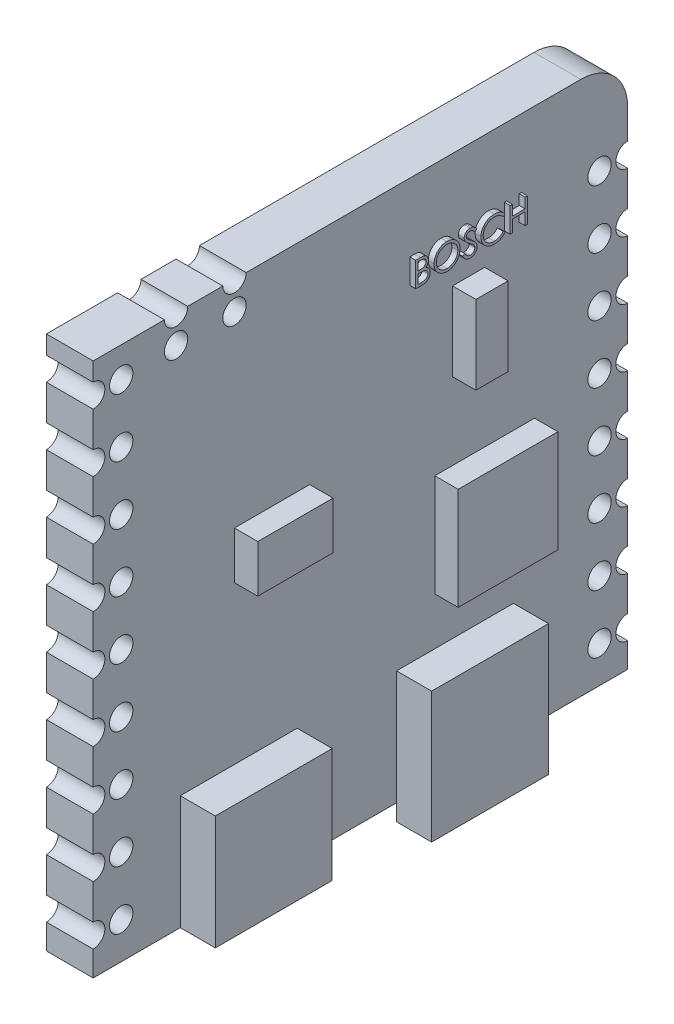
SolidWorks part; units mm, degrees
ref_plane "Front Plane" through (0, 0, 0) normal (0, 0, 1) x (1, 0, 0)
ref_plane "Top Plane" through (0, 0, 0) normal (0, 1, 0) x (1, 0, 0)
ref_plane "Right Plane" through (0, 0, 0) normal (1, 0, 0) x (0, 0, -1)
sketch "Sketch2" plane through (0, 0, 0) normal (1, 0, 0) x (0, 0, -1)
  line L0 (0, 55) -> (0, -55) construction
  line L1 (0, -2.4139) -> (22.86, -2.4139)
  line L2 (0, -2.4139) -> (0, -25.2739)
  line L3 (0, -25.2739) -> (22.86, -25.2739)
  line L4 (22.86, -2.4139) -> (22.86, -25.2739)
  dimension "D1" = 22.86
  dimension "D2" = 22.86
extrude "Boss-Extrude1" add sketch "Sketch2" along normal blind 2
fillet "Fillet1" radius 2 1 edges at (1, -2.4139, -22.86)
sketch "Sketch3" plane through (2, 0, 0) normal (1, 0, 0) x (0, 0, -1)
  line L0 (0, -25.2739) -> (22.86, -25.2739) construction
  line L1 (3.7259, -20.3849) -> (8.7259, -20.3849)
  line L2 (3.7259, -20.3849) -> (3.7259, -25.2739)
  line L3 (3.7259, -25.2739) -> (8.7259, -25.2739)
  line L4 (8.7259, -20.3849) -> (8.7259, -25.2739)
  line L6 (12.9779, -20.3849) -> (17.9779, -20.3849)
  line L7 (12.9779, -20.3849) -> (12.9779, -25.9783)
  line L8 (12.9779, -25.9783) -> (17.9779, -25.9783)
  line L9 (17.9779, -20.3849) -> (17.9779, -25.9783)
  dimension "D1" = 5
  dimension "D2" = 5
  dimension "D3" = 5.5934
extrude "Boss-Extrude2" add sketch "Sketch3" along normal blind 1.5
sketch "Sketch7" plane through (0, -25.9783, 0) normal (0, -1, 0) x (1, 0, 0)
  line L0 (3.5, -12.9779) -> (2, -12.9779) construction
  line L1 (3.2315, -13.4779) -> (2.3, -13.4779)
  line L2 (3.2315, -13.4779) -> (3.2315, -17.5921)
  line L3 (3.2315, -17.5921) -> (2.3, -17.5921)
  line L4 (2.3, -13.4779) -> (2.3, -17.5921)
  line L5 (2, -12.9779) -> (2, -17.9779) construction
  dimension "D1" = 0.5
  dimension "D2" = 0.3
  dimension "D3" = 0.9315
extrude "Cut-Extrude2" cut sketch "Sketch7" against normal blind 5
sketch "Sketch8" plane through (0, -25.2739, 0) normal (0, -1, 0) x (1, 0, 0)
  line L0 (3.5, -3.7259) -> (2, -3.7259) construction
  line L1 (3.2751, -4.2259) -> (2.3451, -4.2259)
  line L2 (3.2751, -4.2259) -> (3.2751, -8.2107)
  line L3 (3.2751, -8.2107) -> (2.3451, -8.2107)
  line L4 (2.3451, -4.2259) -> (2.3451, -8.2107)
  dimension "D1" = 0.5
  dimension "D2" = 0.93
extrude "Cut-Extrude3" cut sketch "Sketch8" against normal blind 4.3
sketch "Sketch9" plane through (2, 0, 0) normal (1, 0, 0) x (0, 0, -1)
  line L0 (0, 1.925) -> (0, -1.925) construction
  circle A1 centre (1.2, -23.704) radius 0.5
  circle A2 centre (0, -23.704) radius 0.5
  dimension "D1" = 1
  dimension "D2" = 1
  dimension "D3" = 1.2
extrude "Cut-Extrude4" cut sketch "Sketch9" against normal through all
pattern_linear "LPattern1" count 9 spacing 2.5 along (0, 1, 0) of "Cut-Extrude4"
ref_plane "Plane1" through (0, 0, -11.43) normal (0, 0, 1) x (1, 0, 0)
mirror "Mirror1" about plane through (0, 0, -11.43) normal (0, 0, 1) of "Cut-Extrude4"
pattern_linear "LPattern2" count 8 spacing 2.5 along (0, 1, 0) of "Mirror1"
sketch "Sketch10" plane through (2, 0, 0) normal (1, 0, 0) x (0, 0, -1)
  line L0 (20.86, -2.4139) -> (0, -2.4139) construction
  circle A0 centre (3.5464, -3.6139) radius 0.5
  circle A1 centre (3.5464, -2.4139) radius 0.5
  dimension "D1" = 1
  dimension "D2" = 1
  dimension "D3" = 1.2
extrude "Cut-Extrude5" cut sketch "Sketch10" against normal through all
pattern_linear "LPattern3" count 2 spacing 2.5 along (0, 0, -1) of "Cut-Extrude5"
sketch "Sketch11" plane through (0, 0, 0) normal (-1, 0, 0) x (0, 0, 1)
  line L1 (-18.0479, -3.7418) -> (-12.0448, -3.7418)
  line L2 (-18.0479, -3.7418) -> (-18.0479, -7.2135)
  line L3 (-18.0479, -7.2135) -> (-12.0448, -7.2135)
  line L4 (-12.0448, -3.7418) -> (-12.0448, -7.2135)
  line L5 (-15.8781, -9.8534) -> (-14.4316, -9.8534)
  line L6 (-15.8781, -9.8534) -> (-15.8781, -12.9635)
  line L7 (-15.8781, -12.9635) -> (-14.4316, -12.9635)
  line L8 (-14.4316, -9.8534) -> (-14.4316, -12.9635)
  line L9 (-8.0668, -21.0641) -> (-4.7759, -21.0641)
  line L10 (-8.0668, -21.0641) -> (-8.0668, -23.8125)
  line L11 (-8.0668, -23.8125) -> (-4.7759, -23.8125)
  line L12 (-4.7759, -21.0641) -> (-4.7759, -23.8125)
  line L13 (-7.4882, -6.888) -> (-4.7759, -6.888)
  line L14 (-7.4882, -6.888) -> (-7.4882, -8.4069)
  line L15 (-7.4882, -8.4069) -> (-4.7759, -8.4069)
  line L16 (-4.7759, -6.888) -> (-4.7759, -8.4069)
  line L17 (-15.8781, -14.2654) -> (-14.4316, -14.2654)
  line L18 (-15.8781, -14.2654) -> (-15.8781, -15.2779)
  line L19 (-15.8781, -15.2779) -> (-14.4316, -15.2779)
  line L20 (-14.4316, -14.2654) -> (-14.4316, -15.2779)
  line L21 (-15.4441, -16.616) -> (-14.6847, -16.616)
  line L22 (-15.4441, -16.616) -> (-15.4441, -18.4242)
  line L23 (-15.4441, -18.4242) -> (-14.6847, -18.4242)
  line L24 (-14.6847, -16.616) -> (-14.6847, -18.4242)
  line L25 (-5.7162, -14.2654) -> (-4.5589, -14.2654)
  line L26 (-5.7162, -14.2654) -> (-5.7162, -16.616)
  line L27 (-5.7162, -16.616) -> (-4.5589, -16.616)
  line L28 (-4.5589, -14.2654) -> (-4.5589, -16.616)
  line L29 (-11.1769, -9.6003) -> (-8.0668, -9.6003)
  line L30 (-11.1769, -9.6003) -> (-11.1769, -11.4084)
  line L31 (-11.1769, -11.4084) -> (-8.0668, -11.4084)
  line L32 (-8.0668, -9.6003) -> (-8.0668, -11.4084)
extrude "Boss-Extrude3" add sketch "Sketch11" along normal blind 1
sketch "Sketch12" plane through (2, 0, 0) normal (1, 0, 0) x (0, 0, -1)
  line L1 (6.0416, -11.6254) -> (9.2602, -11.6254)
  line L2 (6.0416, -11.6254) -> (6.0416, -13.6506)
  line L3 (6.0416, -13.6506) -> (9.2602, -13.6506)
  line L4 (9.2602, -11.6254) -> (9.2602, -13.6506)
  line L5 (14.6124, -13.9761) -> (18.8797, -13.9761)
  line L6 (14.6124, -13.9761) -> (14.6124, -18.3518)
  line L7 (14.6124, -18.3518) -> (18.8797, -18.3518)
  line L8 (18.8797, -13.9761) -> (18.8797, -18.3518)
  line L9 (15.3718, -7.322) -> (16.746, -7.322)
  line L10 (15.3718, -7.322) -> (15.3718, -10.6852)
  line L11 (15.3718, -10.6852) -> (16.746, -10.6852)
  line L12 (16.746, -7.322) -> (16.746, -10.6852)
extrude "Boss-Extrude4" add sketch "Sketch12" along normal blind 1
sketch "Sketch13" plane through (2, 0, 0) normal (1, 0, 0) x (0, 0, -1)
  text T0 "BOSCH" font "Century Gothic" height in points 4
extrude "Boss-Extrude5" add sketch "Sketch13" along normal blind 0.25
